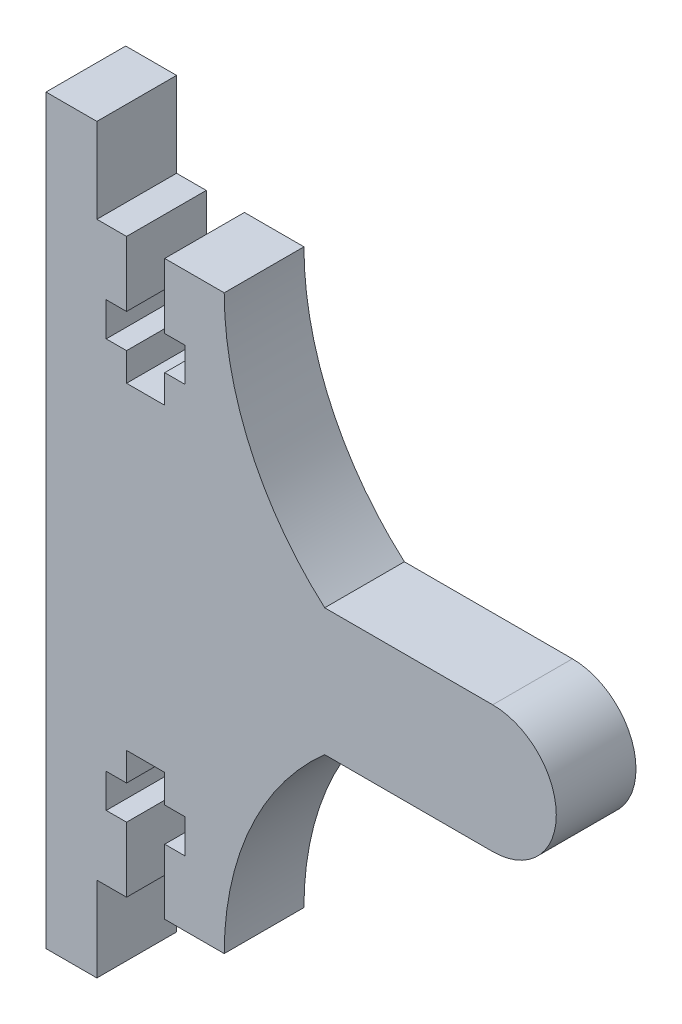
SolidWorks part; units mm, degrees
material "Acrylic (Medium-high impact)"
ref_plane "Front Plane" through (0, 0, 0) normal (0, 0, 1) x (1, 0, 0)
ref_plane "Top Plane" through (0, 0, 0) normal (0, 1, 0) x (1, 0, 0)
ref_plane "Right Plane" through (0, 0, 0) normal (1, 0, 0) x (0, 0, -1)
sketch "Sketch1" plane through (0, 0, 0) normal (0, 0, 1) x (1, 0, 0)
  line L0 (652.8999, 449.103) -> (641.0097, 449.103)
  line L1 (652.8999, 440.103) -> (641.0097, 440.103)
  line L2 (633.8999, 464.853) -> (633.8999, 424.353) construction
  line L3 (629.6883, 424.353) -> (633.8999, 424.353)
  line L4 (629.6883, 428.953) -> (629.6883, 424.353)
  line L5 (631.1282, 428.953) -> (629.6883, 428.953)
  line L6 (631.1282, 431.353) -> (631.1282, 428.953)
  line L7 (629.6883, 431.353) -> (631.1282, 431.353)
  line L8 (629.6883, 433.353) -> (629.6883, 431.353)
  line L9 (626.9883, 433.353) -> (629.6883, 433.353)
  line L10 (626.9883, 431.353) -> (626.9883, 433.353)
  line L11 (625.5484, 431.353) -> (626.9883, 431.353)
  line L12 (625.5484, 428.953) -> (625.5484, 431.353)
  line L13 (626.9883, 428.953) -> (625.5484, 428.953)
  line L14 (626.9883, 424.353) -> (626.9883, 428.953)
  line L15 (624.8883, 424.353) -> (626.9883, 424.353)
  line L16 (624.8883, 418.353) -> (624.8883, 424.353)
  line L17 (621.2883, 464.853) -> (621.2883, 470.853)
  line L18 (621.2883, 470.853) -> (624.8883, 470.853)
  line L19 (624.8883, 470.853) -> (624.8883, 464.853)
  line L20 (624.8883, 464.853) -> (626.9883, 464.853)
  line L21 (626.9883, 464.853) -> (626.9883, 460.253)
  line L22 (626.9883, 460.253) -> (625.5484, 460.253)
  line L23 (625.5484, 460.253) -> (625.5484, 457.8529)
  line L24 (625.5484, 457.8529) -> (626.9883, 457.8529)
  line L25 (626.9883, 457.8529) -> (626.9883, 455.8529)
  line L26 (626.9883, 455.8529) -> (629.6883, 455.8529)
  line L27 (629.6883, 455.8529) -> (629.6883, 457.8529)
  line L28 (629.6883, 457.8529) -> (631.1282, 457.8529)
  line L29 (631.1282, 457.8529) -> (631.1282, 460.253)
  line L30 (631.1282, 460.253) -> (629.6883, 460.253)
  line L31 (629.6883, 460.253) -> (629.6883, 464.853)
  line L32 (629.6883, 464.853) -> (633.8999, 464.853)
  line L33 (621.2883, 418.353) -> (624.8883, 418.353)
  line L34 (-348.8277, 444.603) -> (49651.1723, 444.603) construction
  line L35 (628.3383, -544.1471) -> (628.3383, 49455.8529) construction
  line L36 (621.2883, 424.353) -> (621.2883, 418.353)
  line L38 (652.8999, 449.103) -> (652.8999, 440.103) construction
  line L39 (621.2883, 464.853) -> (621.2883, 424.353)
  line L40 (633.8999, 440.103) -> (652.8999, 440.103) construction
  line L41 (633.8999, 449.103) -> (652.8999, 449.103) construction
  arc A0 (633.8999, 464.853) -> (641.0097, 449.103) centre (654.8999, 464.853) ccw
  arc A1 (633.8999, 424.353) -> (641.0097, 440.103) centre (654.8999, 424.353) cw
  arc A2 (652.8999, 440.103) -> (652.8999, 449.103) centre (652.8999, 444.603) ccw
  point P7 (640.8999, 444.603)
  point P47 (628.3383, 433.353)
  point P49 (621.2883, 444.603)
  point P50 (628.3383, 444.603)
  point P51 (628.3383, 455.8529)
  point P52 (657.3999, 444.603)
  dimension "D5" = 4.6
  dimension "D6" = 2.4001
  dimension "D11" = 21
  dimension "D1" = 6
  dimension "D2" = 3.6
  dimension "D3" = 40.5
  dimension "D4" = 9
  dimension "D7" = 2.1
  dimension "D8" = 2
  dimension "D9" = 2.7
  dimension "D10" = 1.4399
  dimension "D12" = 23.5
extrude "Boss-Extrude1" add sketch "Sketch1" along normal blind 5.64
